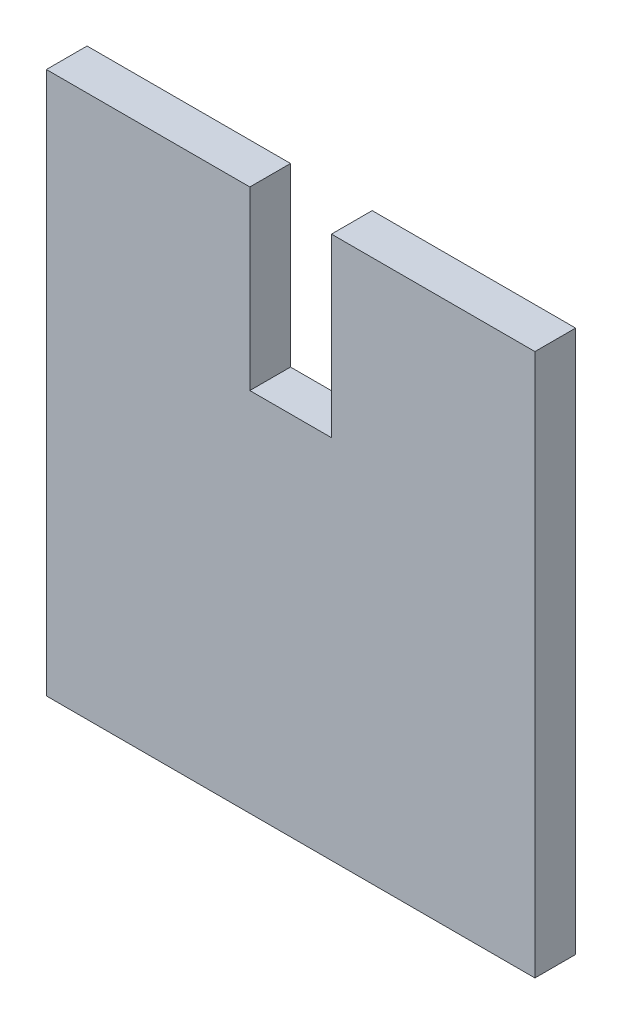
SolidWorks part; units mm, degrees
ref_plane "Front Plane" through (0, 0, 0) normal (0, 0, 1) x (1, 0, 0)
ref_plane "Top Plane" through (0, 0, 0) normal (0, 1, 0) x (1, 0, 0)
ref_plane "Right Plane" through (0, 0, 0) normal (1, 0, 0) x (0, 0, -1)
sketch "Sketch1" plane through (0, 0, 0) normal (0, 0, 1) x (1, 0, 0)
  line L0 (0, 0) -> (0, 80)
  line L1 (0, 80) -> (30, 80)
  line L2 (30, 80) -> (30, 54)
  line L3 (30, 54) -> (42.04, 54)
  line L4 (42.04, 54) -> (42.04, 80)
  line L5 (42.04, 80) -> (72.04, 80)
  line L6 (72.04, 80) -> (72.04, 0)
  line L7 (72.04, 0) -> (0, 0)
  dimension "D1" = 80
  dimension "D2" = 30
  dimension "D3" = 12.04
  dimension "D4" = 26
  dimension "D5" = 26
  dimension "D6" = 30
extrude "Boss-Extrude1" add sketch "Sketch1" along normal blind 6
